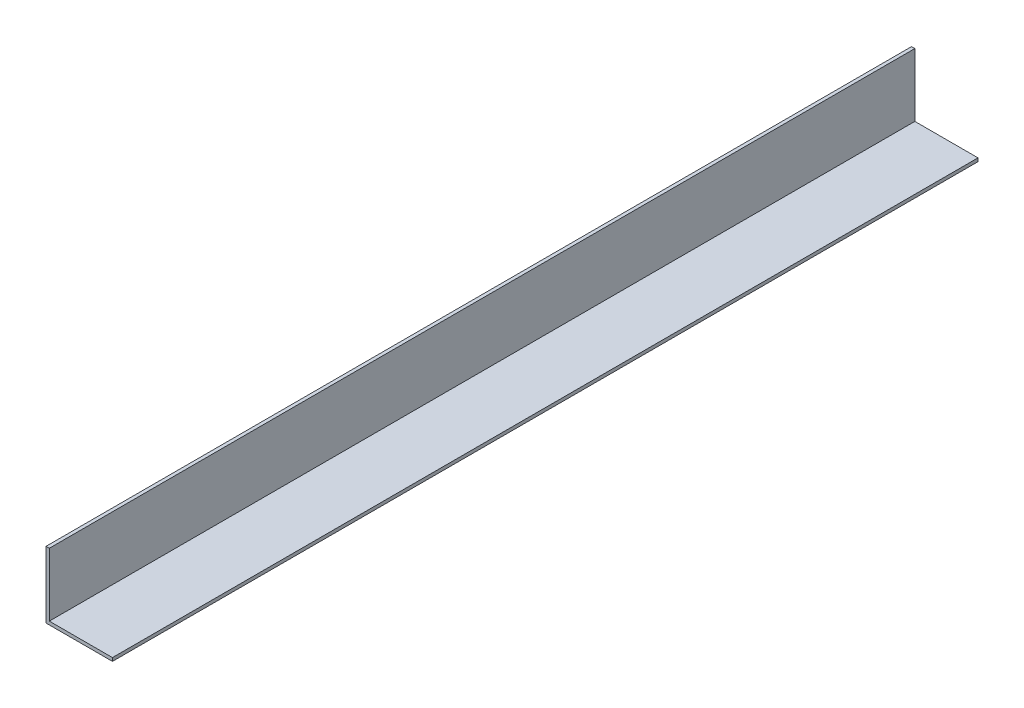
SolidWorks part; units mm, degrees
ref_plane "Front Plane" through (0, 0, 0) normal (0, 0, 1) x (1, 0, 0)
ref_plane "Top Plane" through (0, 0, 0) normal (0, 1, 0) x (1, 0, 0)
ref_plane "Right Plane" through (0, 0, 0) normal (1, 0, 0) x (0, 0, -1)
sketch "Sketch1" plane through (0, 0, 0) normal (0, 0, 1) x (1, 0, 0)
  line L0 (0, 0) -> (0, 40)
  line L1 (0, 0) -> (40, 0)
  line L2 (2, 2) -> (40, 2)
  line L3 (2, 2) -> (2, 40)
  line L4 (0, 40) -> (2, 40)
  line L5 (40, 2) -> (40, 0)
  dimension "D1" = 40
  dimension "D2" = 2
extrude "Boss-Extrude1" add sketch "Sketch1" along normal blind 521
equation "\"CarBeamWidth\"=700.0"
equation "\"WheelWidth\"=650.0"
equation "\"Wheel_FrontBoxDistance\"=1390.0"
equation "\"MetalSheet_3mm_length\"=5030.0"
equation "\"MetalSheet_3mm_width\"=1923.0"
equation "\"MetalSheet_3mm_FloorCut_L_length\"=1764.0"
equation "\"MetalSheet_3mm_FloorCut_L_disdance\"=1665.0"
equation "\"MetalSheet_3mm_FloorCut_R_length\"=1764.0"
equation "\"MetalSheet_3mm_FloorCut_R_disdance\"=1665.0"
equation "\"indoorHeight\"=1940.0"
equation "\"indoorHeight_para\"=25.0"
equation "\"rearLightHeight_para\"=265.0"
equation "\"haveDoor_R\"=1"
equation "\"side_door_bottom_R_3mm_length\"=1934.0"
equation "\"side_door_bottom_R_3mm_toFrontDistance\"=1583.0"
equation "\"1Bar_Side_RF_3mm_length\"=1493.0"
equation "\"1Bar_Side_RB_3mm_length\"=1493.0"
equation "\"DoorSeparator_RF_3mm_withHinge_toFrontDistance\"=1673.0"
equation "\"DoorSeparator_RF_3mm_withHinge_exist\"=1"
equation "\"DoorSeparator_RB_3mm_withHinge_toFrontDistance\"=3427.0"
equation "\"DoorSeparator_RB_3mm_withHinge_exist\"=1"
equation "\"Door_R1_L_open_Single_toFrontDistance\"=2547.5"
equation "\"Door_R1_L_open_Single_exist\"=1"
equation "\"door_base_long7_R1_L_open_Single_height\"=1890.0"
equation "\"door_base_short7_R1_L_open_Single_height\"=1890.0"
equation "\"door_base_short7_R1_L_open_Single_width\"=864"
equation "\"Door_R1_R_open_Single_toFrontDistance\"=3422.0"
equation "\"Door_R1_R_open_Single_exist\"=1"
equation "\"door_base_long7_R1_R_open_Single_height\"=1890.0"
equation "\"door_base_short7_R1_R_open_Single_height\"=1890.0"
equation "\"door_base_short7_R1_R_open_Single_width\"=864"
equation "\"x\"=66.0"
equation "\"da\"=62.0"
equation "\"SquareTube_length\"=1923.0"
equation "\"channelSteel_length\"=5030.0"
equation "\"SquareTube_inFront_AvgDistance\"=285.0"
equation "\"SquareTube_inFront_TotalCount\"=5"
equation "\"SquareTube_inFront1_cutDepth50_R\"=0.5"
equation "\"SquareTube_inFront1_cutDepth50_L\"=0.5"
equation "\"SquareTube_inFront2_cutDepth50_R\"=0.5"
equation "\"SquareTube_inFront2_cutDepth50_L\"=0.5"
equation "\"SquareTube_inFront3_cutDepth50_R\"=0.5"
equation "\"SquareTube_inFront3_cutDepth50_L\"=0.5"
equation "\"SquareTube_inFront4_cutDepth50_R\"=0.5"
equation "\"SquareTube_inFront4_cutDepth50_L\"=0.5"
equation "\"SquareTube_inFront5_cutDepth50_R\"=50"
equation "\"SquareTube_inFront5_cutDepth50_L\"=50"
equation "\"SquareTube_inFront6_cutDepth50_R\"=50"
equation "\"SquareTube_inFront6_cutDepth50_L\"=50"
equation "\"SquareTube_inFront7_cutDepth50_R\"=50"
equation "\"SquareTube_inFront7_cutDepth50_L\"=50"
equation "\"SquareTube_inFront8_cutDepth50_R\"=50"
equation "\"SquareTube_inFront8_cutDepth50_L\"=50"
equation "\"SquareTube_inFront9_cutDepth50_R\"=50"
equation "\"SquareTube_inFront9_cutDepth50_L\"=50"
equation "\"SquareTube_inFront10_cutDepth50_R\"=50"
equation "\"SquareTube_inFront10_cutDepth50_L\"=50"
equation "\"SquareTube_inFront11_cutDepth50_R\"=50"
equation "\"SquareTube_inFront11_cutDepth50_L\"=50"
equation "\"SquareTube_inFront12_cutDepth50_R\"=50"
equation "\"SquareTube_inFront12_cutDepth50_L\"=50"
equation "\"SquareTube_inFront13_cutDepth50_R\"=50"
equation "\"SquareTube_inFront13_cutDepth50_L\"=50"
equation "\"SquareTube_inFront14_cutDepth50_R\"=50"
equation "\"SquareTube_inFront14_cutDepth50_L\"=50"
equation "\"SquareTube_inBack_AvgDistance\"=333.125"
equation "\"SquareTube_inBack_TotalCount\"=9"
equation "\"SquareTube_inBack1_cutDepth50_R\"=50"
equation "\"SquareTube_inBack1_cutDepth50_L\"=50"
equation "\"SquareTube_inBack2_cutDepth50_R\"=50"
equation "\"SquareTube_inBack2_cutDepth50_L\"=50"
equation "\"SquareTube_inBack3_cutDepth50_R\"=50"
equation "\"SquareTube_inBack3_cutDepth50_L\"=50"
equation "\"SquareTube_inBack4_cutDepth50_R\"=50"
equation "\"SquareTube_inBack4_cutDepth50_L\"=50"
equation "\"SquareTube_inBack5_cutDepth50_R\"=50"
equation "\"SquareTube_inBack5_cutDepth50_L\"=50"
equation "\"SquareTube_inBack6_cutDepth50_R\"=0.5"
equation "\"SquareTube_inBack6_cutDepth50_L\"=0.5"
equation "\"SquareTube_inBack7_cutDepth50_R\"=0.5"
equation "\"SquareTube_inBack7_cutDepth50_L\"=0.5"
equation "\"SquareTube_inBack8_cutDepth50_R\"=0.5"
equation "\"SquareTube_inBack8_cutDepth50_L\"=0.5"
equation "\"boxLength\"=5100.0"
equation "\"boxWidth\"=1930.0"
equation "\"D1@Boss-Extrude1\"= ( ( \"boxWidth\" - \"CarBeamWidth\" - 6 - 6 ) / 2 ) - 88"
